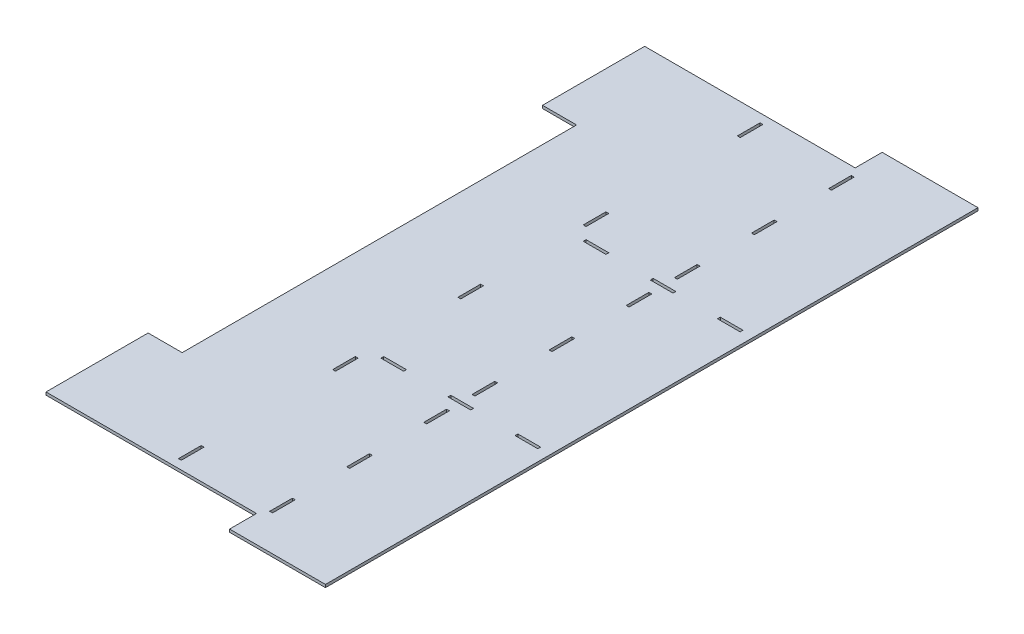
SolidWorks part; units mm, degrees
material "6061-T6 (SS)"
ref_plane "X-Y Datum" through (0, 0, 0) normal (0, 0, 1) x (1, 0, 0)
ref_plane "X-Z Datum" through (0, 0, 0) normal (0, 1, 0) x (1, 0, 0)
ref_plane "Y-Z Datum" through (0, 0, 0) normal (1, 0, 0) x (0, 0, -1)
sketch "Sketch2" plane through (0, 0, 0) normal (0, 1, 0) x (1, 0, 0)
  line L0 (204.155, 220.1367) -> (204.155, 223.3117)
  line L1 (0, 0) -> (95.7275, 0)
  line L2 (0, 0) -> (0, 216.9617)
  line L3 (0, 216.9617) -> (95.7275, 216.9617)
  line L4 (95.7275, 0) -> (95.7275, 216.9617)
  line L5 (95.7275, 216.9617) -> (98.9025, 216.9617)
  line L6 (95.7275, 216.9617) -> (95.7275, 0)
  line L7 (95.7275, 0) -> (98.9025, 0)
  line L8 (98.9025, 216.9617) -> (98.9025, 0)
  line L9 (98.9025, 216.9617) -> (102.0775, 216.9617)
  line L10 (98.9025, 216.9617) -> (98.9025, 0)
  line L11 (98.9025, 0) -> (102.0775, 0)
  line L12 (100.49, 216.9617) -> (100.49, 0)
  line L17 (0, 216.9617) -> (200.98, 216.9617)
  line L18 (0, 216.9617) -> (0, 220.1367)
  line L19 (0, 220.1367) -> (200.98, 220.1367)
  line L20 (100.49, 216.9617) -> (100.49, 220.1367)
  line L21 (0, 220.1367) -> (-3.175, 220.1367)
  line L22 (0, 220.1367) -> (0, 0)
  line L23 (0, 0) -> (-3.175, 0)
  line L24 (-3.175, 220.1367) -> (-3.175, 0)
  line L25 (-3.175, 0) -> (204.155, 0)
  line L26 (-3.175, 0) -> (-3.175, -3.175)
  line L27 (-3.175, -3.175) -> (204.155, -3.175)
  line L28 (100.49, 0) -> (100.49, -3.175)
  line L29 (-3.175, 220.1367) -> (204.155, 220.1367)
  line L30 (-3.175, 220.1367) -> (-3.175, 223.3117)
  line L31 (-3.175, 221.7242) -> (204.155, 221.7242)
  line L32 (100.49, 220.1367) -> (100.49, 223.3117)
  line L33 (200.98, 216.9617) -> (200.98, 220.1367)
  line L34 (102.0775, 216.9617) -> (102.0775, 0)
  line L35 (105.2525, 0) -> (102.0775, 0)
  line L36 (102.0775, 216.9617) -> (102.0775, 0)
  line L37 (105.2525, 216.9617) -> (102.0775, 216.9617)
  line L38 (105.2525, 216.9617) -> (105.2525, 0)
  line L39 (204.155, 0) -> (204.155, -3.175)
  line L40 (200.98, 216.9617) -> (105.2525, 216.9617)
  line L41 (105.2525, 0) -> (105.2525, 216.9617)
  line L42 (200.98, 0) -> (105.2525, 0)
  line L43 (200.98, 0) -> (200.98, 216.9617)
  line L44 (200.98, 0) -> (204.155, 0)
  line L45 (204.155, 220.1367) -> (204.155, 0)
  line L46 (200.98, 220.1367) -> (204.155, 220.1367)
  line L47 (200.98, 220.1367) -> (200.98, 0)
  line L48 (200.98, 223.3117) -> (200.98, 443.4484)
  line L49 (221.8451, -3.175) -> (221.8451, 221.7242) construction
  line L50 (200.98, 223.3117) -> (204.155, 223.3117)
  line L51 (204.155, 223.3117) -> (204.155, 443.4484)
  line L52 (200.98, 443.4484) -> (204.155, 443.4484)
  line L53 (200.98, 443.4484) -> (200.98, 226.4867)
  line L54 (200.98, 443.4484) -> (105.2525, 443.4484)
  line L55 (105.2525, 443.4484) -> (105.2525, 226.4867)
  line L56 (200.98, 226.4867) -> (105.2525, 226.4867)
  line L57 (204.155, 443.4484) -> (204.155, 446.6234)
  line L58 (105.2525, 226.4867) -> (105.2525, 443.4484)
  line L59 (105.2525, 226.4867) -> (102.0775, 226.4867)
  line L60 (102.0775, 226.4867) -> (102.0775, 443.4484)
  line L61 (105.2525, 443.4484) -> (102.0775, 443.4484)
  line L62 (102.0775, 226.4867) -> (102.0775, 443.4484)
  line L63 (200.98, 226.4867) -> (200.98, 223.3117)
  line L64 (-3.175, 223.3117) -> (204.155, 223.3117)
  line L65 (100.49, 443.4484) -> (100.49, 446.6234)
  line L66 (-3.175, 446.6234) -> (204.155, 446.6234)
  line L67 (-3.175, 443.4484) -> (-3.175, 446.6234)
  line L68 (-3.175, 443.4484) -> (204.155, 443.4484)
  line L69 (-3.175, 223.3117) -> (-3.175, 443.4484)
  line L70 (0, 443.4484) -> (-3.175, 443.4484)
  line L71 (0, 223.3117) -> (0, 443.4484)
  line L72 (0, 223.3117) -> (-3.175, 223.3117)
  line L73 (100.49, 226.4867) -> (100.49, 223.3117)
  line L74 (0, 223.3117) -> (200.98, 223.3117)
  line L75 (0, 226.4867) -> (0, 223.3117)
  line L76 (0, 226.4867) -> (200.98, 226.4867)
  line L77 (100.49, 226.4867) -> (100.49, 443.4484)
  line L78 (98.9025, 443.4484) -> (102.0775, 443.4484)
  line L79 (98.9025, 226.4867) -> (98.9025, 443.4484)
  line L80 (98.9025, 226.4867) -> (102.0775, 226.4867)
  line L81 (98.9025, 226.4867) -> (98.9025, 443.4484)
  line L82 (95.7275, 443.4484) -> (98.9025, 443.4484)
  line L83 (95.7275, 226.4867) -> (95.7275, 443.4484)
  line L84 (95.7275, 226.4867) -> (98.9025, 226.4867)
  line L85 (95.7275, 443.4484) -> (95.7275, 226.4867)
  line L86 (0, 226.4867) -> (95.7275, 226.4867)
  line L87 (0, 443.4484) -> (0, 226.4867)
  line L88 (0, 443.4484) -> (95.7275, 443.4484)
  line L90 (-3.175, 446.6234) -> (204.155, 446.6234)
  line L91 (-3.175, 446.6234) -> (-3.175, 449.7984)
  line L92 (-3.175, 448.2109) -> (204.155, 448.2109)
  line L93 (204.155, 446.6234) -> (204.155, 449.7984)
  line L94 (100.49, 669.9352) -> (100.49, 673.1102)
  line L95 (0, 669.9352) -> (200.98, 669.9352)
  line L96 (105.2525, 669.9352) -> (102.0775, 669.9352)
  line L97 (-3.175, 673.1102) -> (204.155, 673.1102)
  line L98 (200.98, 673.1102) -> (204.155, 673.1102)
  line L99 (200.98, 669.9352) -> (105.2525, 669.9352)
  line L100 (200.98, 452.9734) -> (204.155, 452.9734)
  line L101 (204.155, 673.1102) -> (204.155, 452.9734)
  line L102 (200.98, 673.1102) -> (200.98, 452.9734)
  line L103 (204.155, 452.9734) -> (204.155, 449.7984)
  line L104 (105.2525, 452.9734) -> (105.2525, 669.9352)
  line L105 (-3.175, 452.9734) -> (204.155, 452.9734)
  line L106 (105.2525, 452.9734) -> (102.0775, 452.9734)
  line L107 (102.0775, 669.9352) -> (102.0775, 452.9734)
  line L108 (100.49, 669.9352) -> (100.49, 452.9734)
  line L109 (95.7275, 669.9352) -> (95.7275, 452.9734)
  line L110 (98.9025, 669.9352) -> (98.9025, 452.9734)
  line L111 (100.49, 452.9734) -> (100.49, 449.7984)
  line L112 (0, 673.1102) -> (0, 452.9734)
  line L113 (-3.175, 673.1102) -> (-3.175, 452.9734)
  line L114 (-3.175, 452.9734) -> (-3.175, 449.7984)
  line L115 (-3.175, 449.7984) -> (204.155, 449.7984)
  line L116 (-3.175, 673.1102) -> (204.155, 673.1102)
  line L117 (-3.175, 673.1102) -> (-3.175, 676.2852)
  line L118 (-3.175, 676.2852) -> (204.155, 676.2852)
  line L119 (204.155, 673.1102) -> (204.155, 676.2852)
  point P41 (100.49, 221.7242)
  dimension "D1" = 95.7275
  dimension "D2" = 216.9617
  dimension "D3" = 3.175
  dimension "D4" = 1.5875
  dimension "D5" = 1.5875
  dimension "D6" = 3.175
  dimension "D7" = 3.175
  dimension "D8" = 3.175
  dimension "D9" = 1.5875
  dimension "D10" = 3.175
sketch "Sketch3" plane through (0, 0, 0) normal (0, 1, 0) x (1, 0, 0)
  line L0 (-103.82, 448.2109) -> (12.7, 448.2109) construction
  line L2 (-103.82, 669.9352) -> (-103.82, 0)
  line L3 (-103.82, 0) -> (200.98, 0)
  line L4 (200.98, 669.9352) -> (200.98, 0)
  line L5 (-3.175, 448.2109) -> (204.155, 448.2109) construction
  line L6 (200.98, 448.2109) -> (188.28, 448.2109) construction
  line L7 (-3.175, 449.7984) -> (204.155, 449.7984) construction
  line L8 (12.7, 449.7984) -> (38.1, 449.7984)
  line L9 (12.7, 449.7984) -> (12.7, 446.6234)
  line L10 (12.7, 446.6234) -> (38.1, 446.6234)
  line L11 (38.1, 449.7984) -> (38.1, 446.6234)
  line L12 (-3.175, 446.6234) -> (204.155, 446.6234) construction
  line L13 (100.49, 673.1102) -> (100.49, 660.4102) construction
  line L14 (188.28, 449.7984) -> (162.88, 449.7984)
  line L15 (188.28, 449.7984) -> (188.28, 446.6234)
  line L16 (188.28, 446.6234) -> (162.88, 446.6234)
  line L17 (162.88, 449.7984) -> (162.88, 446.6234)
  line L18 (87.79, 446.6234) -> (113.19, 446.6234)
  line L19 (87.79, 446.6234) -> (87.79, 449.7984)
  line L20 (87.79, 449.7984) -> (113.19, 449.7984)
  line L21 (113.19, 446.6234) -> (113.19, 449.7984)
  line L22 (87.79, 446.6234) -> (113.19, 449.7984) construction
  line L23 (87.79, 449.7984) -> (113.19, 446.6234) construction
  line L24 (100.49, 669.9352) -> (100.49, 452.9734) construction
  line L25 (98.9025, 669.9352) -> (98.9025, 452.9734) construction
  line L26 (98.9025, 660.4102) -> (102.0775, 660.4102)
  line L27 (98.9025, 660.4102) -> (98.9025, 635.0102)
  line L28 (98.9025, 635.0102) -> (102.0775, 635.0102)
  line L29 (102.0775, 660.4102) -> (102.0775, 635.0102)
  line L30 (102.0775, 669.9352) -> (102.0775, 452.9734) construction
  line L31 (100.49, 449.7984) -> (100.49, 462.4984) construction
  line L32 (100.49, 635.0102) -> (100.49, 487.8984) construction
  line L33 (102.0775, 462.4984) -> (98.9025, 462.4984)
  line L34 (102.0775, 462.4984) -> (102.0775, 487.8984)
  line L35 (102.0775, 487.8984) -> (98.9025, 487.8984)
  line L36 (98.9025, 462.4984) -> (98.9025, 487.8984)
  line L37 (-14.5216, 448.2109) -> (228.7454, 448.2109) construction
  line L38 (98.9025, 548.7543) -> (102.0775, 548.7543)
  line L39 (98.9025, 548.7543) -> (98.9025, 574.1543)
  line L40 (98.9025, 574.1543) -> (102.0775, 574.1543)
  line L41 (102.0775, 548.7543) -> (102.0775, 574.1543)
  line L42 (98.9025, 548.7543) -> (102.0775, 574.1543) construction
  line L43 (98.9025, 574.1543) -> (102.0775, 548.7543) construction
  line L44 (102.0775, 408.5234) -> (98.9025, 408.5234)
  line L45 (98.9025, 433.9234) -> (98.9025, 408.5234)
  line L46 (102.0775, 433.9234) -> (98.9025, 433.9234)
  line L47 (102.0775, 433.9234) -> (102.0775, 408.5234)
  line L48 (98.9025, 322.2676) -> (102.0775, 322.2676)
  line L49 (102.0775, 347.6676) -> (102.0775, 322.2676)
  line L50 (98.9025, 347.6676) -> (102.0775, 347.6676)
  line L51 (98.9025, 347.6676) -> (98.9025, 322.2676)
  line L52 (98.9025, 261.4117) -> (102.0775, 261.4117)
  line L53 (102.0775, 236.0117) -> (102.0775, 261.4117)
  line L54 (98.9025, 236.0117) -> (102.0775, 236.0117)
  line L55 (98.9025, 236.0117) -> (98.9025, 261.4117)
  line L56 (-103.82, 221.7242) -> (-103.82, 448.2109) construction
  line L57 (-3.175, 221.7242) -> (204.155, 221.7242) construction
  line L58 (-3.175, 223.3117) -> (204.155, 223.3117) construction
  line L59 (12.7, 223.3117) -> (38.1, 223.3117)
  line L60 (12.7, 223.3117) -> (12.7, 220.1367)
  line L61 (12.7, 220.1367) -> (38.1, 220.1367)
  line L62 (38.1, 223.3117) -> (38.1, 220.1367)
  line L63 (0, 220.1367) -> (200.98, 220.1367) construction
  line L64 (-6.8668, 221.7242) -> (213.4812, 221.7242) construction
  line L65 (87.79, 220.1367) -> (113.19, 220.1367)
  line L66 (87.79, 220.1367) -> (87.79, 223.3117)
  line L67 (87.79, 223.3117) -> (113.19, 223.3117)
  line L68 (113.19, 220.1367) -> (113.19, 223.3117)
  line L69 (87.79, 220.1367) -> (113.19, 223.3117) construction
  line L70 (87.79, 223.3117) -> (113.19, 220.1367) construction
  line L71 (188.28, 223.3117) -> (162.88, 223.3117)
  line L72 (188.28, 223.3117) -> (188.28, 220.1367)
  line L73 (188.28, 220.1367) -> (162.88, 220.1367)
  line L74 (162.88, 223.3117) -> (162.88, 220.1367)
  line L75 (102.0775, 9.525) -> (102.0775, 34.925)
  line L76 (102.0775, 9.525) -> (98.9025, 9.525)
  line L77 (98.9025, 9.525) -> (98.9025, 34.925)
  line L78 (102.0775, 34.925) -> (98.9025, 34.925)
  line L79 (98.9025, 95.7809) -> (98.9025, 121.1809)
  line L80 (98.9025, 95.7809) -> (102.0775, 95.7809)
  line L81 (102.0775, 95.7809) -> (102.0775, 121.1809)
  line L82 (98.9025, 121.1809) -> (102.0775, 121.1809)
  line L83 (98.9025, 207.4367) -> (98.9025, 182.0367)
  line L84 (98.9025, 207.4367) -> (102.0775, 207.4367)
  line L85 (102.0775, 207.4367) -> (102.0775, 182.0367)
  line L86 (98.9025, 182.0367) -> (102.0775, 182.0367)
  line L87 (98.9025, 635.0102) -> (102.0775, 660.4102) construction
  line L88 (-103.82, 669.9352) -> (200.98, 669.9352)
  line L89 (98.9025, 462.4984) -> (102.0775, 487.8984) construction
  line L90 (98.9025, 322.2676) -> (102.0775, 347.6676) construction
  line L91 (98.9025, 182.0367) -> (102.0775, 207.4367) construction
  line L92 (-3.1801, 660.4102) -> (-3.1801, 635.0102)
  line L93 (-0.0051, 660.4102) -> (-0.0051, 635.0102)
  line L94 (-3.1801, 660.4102) -> (-0.0051, 660.4102)
  line L95 (-3.1801, 635.0102) -> (-0.0051, 635.0102)
  line L96 (-3.1801, 462.4984) -> (-3.1801, 487.8984)
  line L97 (-0.0051, 487.8984) -> (-3.1801, 487.8984)
  line L98 (-0.0051, 462.4984) -> (-0.0051, 487.8984)
  line L99 (-0.0051, 462.4984) -> (-3.1801, 462.4984)
  line L100 (-0.0051, 347.6676) -> (-0.0051, 322.2676)
  line L101 (-3.1801, 347.6676) -> (-3.1801, 322.2676)
  line L102 (-3.1801, 347.6676) -> (-0.0051, 347.6676)
  line L103 (-3.1801, 322.2676) -> (-0.0051, 322.2676)
  line L104 (-3.1801, 207.4367) -> (-3.1801, 182.0367)
  line L105 (-3.1801, 207.4367) -> (-0.0051, 207.4367)
  line L106 (-0.0051, 207.4367) -> (-0.0051, 182.0367)
  line L107 (-3.1801, 182.0367) -> (-0.0051, 182.0367)
  line L108 (-3.1801, 9.525) -> (-3.1801, 34.925)
  line L109 (-0.0051, 9.525) -> (-0.0051, 34.925)
  line L110 (-0.0051, 34.925) -> (-3.1801, 34.925)
  line L111 (-0.0051, 9.525) -> (-3.1801, 9.525)
  point P0 (100.49, 647.7102)
  point P3 (100.49, 475.1984)
  point P4 (100.49, 334.9676)
  point P24 (100.49, 448.2109)
  point P51 (100.49, 561.4543)
  point P81 (100.49, 221.7242)
  point P107 (100.49, 194.7367)
  point P108 (100.49, 22.225)
  dimension "D1" = 12.7
  dimension "D2" = 25.4
  dimension "D3" = 304.8
  dimension "D4" = 172.5117
  dimension "D5" = 140.2309
  dimension "D6" = 25.4
  dimension "D7" = 2
  dimension "D8" = 98.9076
extrude "Boss-Extrude1" add sketch "Sketch3" along normal blind 3.175
sketch "Sketch6" plane through (0, 3.175, 0) normal (0, 1, 0) x (1, 0, 0)
  line L0 (-103.82, 334.9676) -> (299.5719, 334.9676) construction
  line L5 (200.98, 0) -> (93.6929, 0)
  line L6 (200.98, 0) -> (200.98, -30.1625)
  line L7 (200.98, -30.1625) -> (93.6929, -30.1625)
  line L8 (93.6929, 0) -> (93.6929, -30.1625)
  line L17 (-103.82, 669.9352) -> (-103.82, 0) construction
  line L18 (200.98, 700.0977) -> (93.6929, 700.0977)
  line L19 (93.6929, 669.9352) -> (93.6929, 700.0977)
  line L20 (200.98, 669.9352) -> (93.6929, 669.9352)
  line L21 (200.98, 669.9352) -> (200.98, 700.0977)
  line L26 (-103.82, 555.6352) -> (-141.92, 555.6352)
  line L27 (-103.82, 0) -> (-141.92, 0)
  line L28 (-103.82, 0) -> (-103.82, 114.3)
  line L29 (-103.82, 114.3) -> (-141.92, 114.3)
  line L30 (-141.92, 0) -> (-141.92, 114.3)
  line L31 (-103.82, 669.9352) -> (-103.82, 555.6352)
  line L32 (-103.82, 669.9352) -> (-141.92, 669.9352)
  line L33 (-141.92, 669.9352) -> (-141.92, 555.6352)
  dimension "D1" = 30.1625
  dimension "D2" = 107.2871
  dimension "D3" = 114.3
  dimension "D4" = 38.1
extrude "Boss-Extrude2" add sketch "Sketch6" against normal blind 3.175 contours L20 L21 L18 L19 | L5 L8 L7 L6 | L32 L33 L26 L31 | L30 L27 L28 L29
